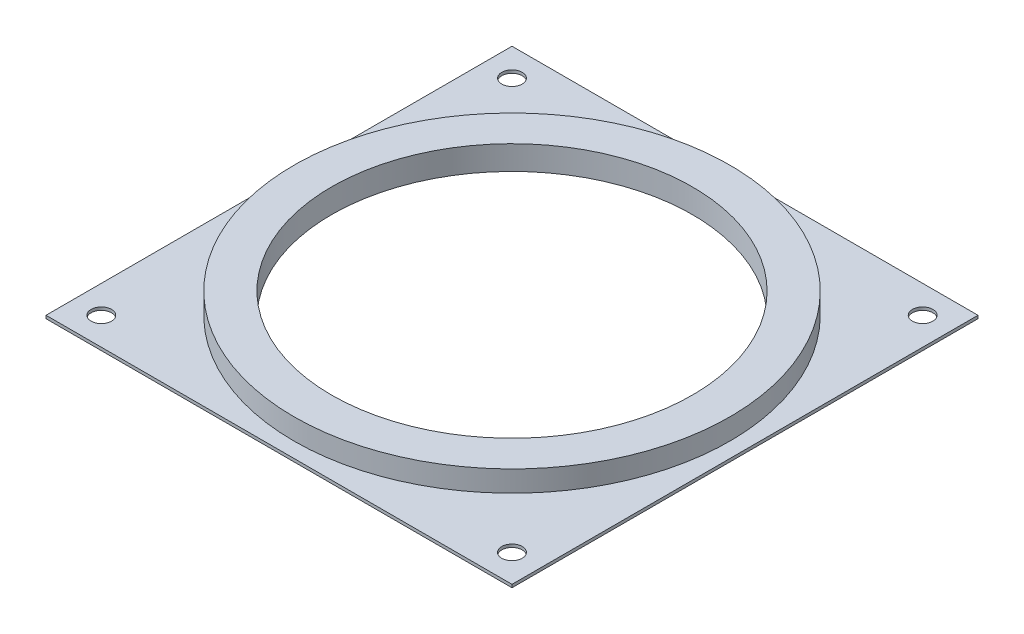
SolidWorks part; units mm, degrees
ref_plane "Front Plane" through (0, 0, 0) normal (0, 0, 1) x (1, 0, 0)
ref_plane "Top Plane" through (0, 0, 0) normal (0, 1, 0) x (1, 0, 0)
ref_plane "Right Plane" through (0, 0, 0) normal (1, 0, 0) x (0, 0, -1)
sketch "Sketch1" plane through (0, 0, 0) normal (0, 1, 0) x (1, 0, 0)
  line L0 (0, 22.5998) -> (0, -23.5171) construction
  line L1 (-77.5, 77.5) -> (77.5, 77.5)
  line L2 (-77.5, 77.5) -> (-77.5, -77.5)
  line L3 (-77.5, -77.5) -> (77.5, -77.5)
  line L4 (77.5, 77.5) -> (77.5, -77.5)
  line L5 (-77.5, 77.5) -> (77.5, -77.5) construction
  line L6 (-77.5, -77.5) -> (77.5, 77.5) construction
  line L7 (-27.5294, 0) -> (43.8489, 0) construction
  circle A0 centre (0, 0) radius 60
  circle A1 centre (-68.3, 68.3) radius 3.4
  circle A5 centre (68.3, 68.3) radius 3.4
  circle A6 centre (-68.3, -68.3) radius 3.4
  circle A7 centre (68.3, -68.3) radius 3.4
  point P0 (0, 0)
  point P19 (0.8915, 0)
  dimension "D3" = 120
  dimension "D4" = 6.8
  dimension "D1" = 155
  dimension "D2" = 155
  dimension "D5" = 9.2
extrude "Boss-Extrude1" add sketch "Sketch1" along normal blind 1
sketch "Sketch2" plane through (0, 1, 0) normal (0, 1, 0) x (1, 0, 0)
  line L4 (77.5, -77.5) -> (77.5, 77.5)
  line L5 (77.5, 77.5) -> (-77.5, 77.5)
  line L6 (-77.5, 77.5) -> (-77.5, -77.5)
  line L7 (-77.5, -77.5) -> (77.5, -77.5)
  line L8 (77.5, -77.5) -> (77.5, 77.5)
  line L9 (77.5, 77.5) -> (-77.5, 77.5)
  line L10 (-77.5, 77.5) -> (-77.5, -77.5)
  line L11 (-77.5, -77.5) -> (77.5, -77.5)
  circle A0 centre (0, 0) radius 60
  circle A1 centre (0, 0) radius 72.5
  circle M11 centre (0, 0) radius 60
  dimension "D2" = 120
  dimension "D3" = 145
  dimension "D1" = 0
extrude "Boss-Extrude2" add sketch "Sketch2" along normal blind 7 contours A1 M11
